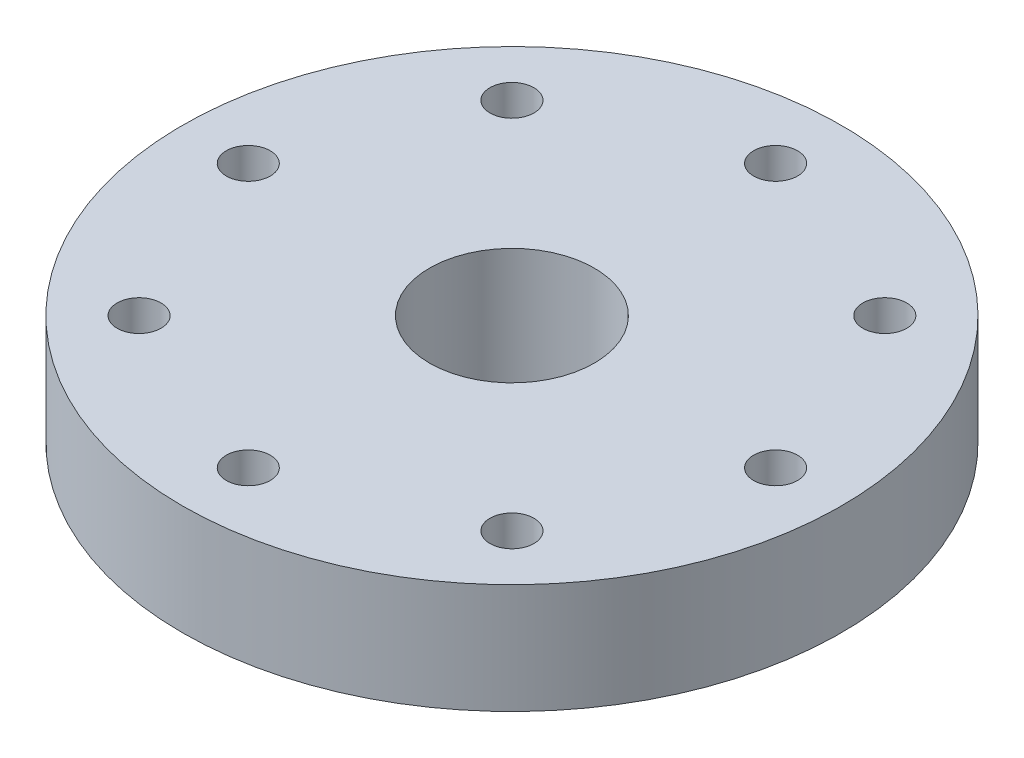
SolidWorks part; units mm, degrees
ref_plane "Front Plane" through (0, 0, 0) normal (0, 0, 1) x (1, 0, 0)
ref_plane "Top Plane" through (0, 0, 0) normal (0, 1, 0) x (1, 0, 0)
ref_plane "Right Plane" through (0, 0, 0) normal (1, 0, 0) x (0, 0, -1)
sketch "Sketch1" plane through (0, 0, 0) normal (0, 1, 0) x (1, 0, 0)
  circle A0 centre (0, 0) radius 6
  dimension "D1" = 12
extrude "Boss-Extrude1" add sketch "Sketch1" along normal blind 1.3
sketch "Sketch2" plane through (0, 1.3, 0) normal (0, 1, 0) x (1, 0, 0)
  line L0 (0, 13) -> (0, 15) construction
  circle A0 centre (0, 0) radius 15
  circle A1 centre (0, 12) radius 1
  circle A2 centre (8.4853, 8.4853) radius 1
  circle A3 centre (12, 0) radius 1
  circle A4 centre (8.4853, -8.4853) radius 1
  circle A5 centre (0, -12) radius 1
  circle A6 centre (-8.4853, -8.4853) radius 1
  circle A7 centre (-12, 0) radius 1
  circle A8 centre (-8.4853, 8.4853) radius 1
  point P23 (0, 0)
  dimension "D1" = 30
  dimension "D2" = 2
  dimension "D3" = 2
extrude "Boss-Extrude2" add sketch "Sketch2" along normal blind 5
sketch "Sketch3" plane through (0, 0, 0) normal (0, -1, 0) x (1, 0, 0)
  circle A0 centre (0, 0) radius 2
  dimension "D1" = 4
extrude "Cut-Extrude1" cut sketch "Sketch3" against normal through all
sketch "Sketch4" plane through (0, 6.3, 0) normal (0, 1, 0) x (1, 0, 0)
  circle A0 centre (0, 0) radius 3.75
  dimension "D1" = 7.5
extrude "Cut-Extrude2" cut sketch "Sketch4" against normal blind 5.6
